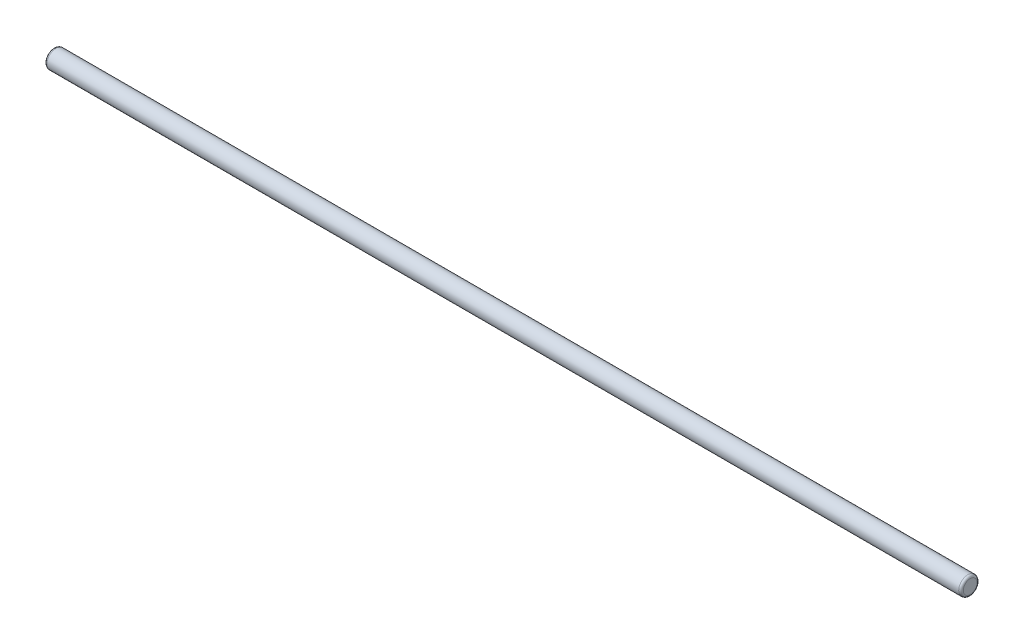
SolidWorks part; units mm, degrees
ref_plane "Front Plane" through (0, 0, 0) normal (0, 0, 1) x (1, 0, 0)
ref_plane "Top Plane" through (0, 0, 0) normal (0, 1, 0) x (1, 0, 0)
ref_plane "Right Plane" through (0, 0, 0) normal (1, 0, 0) x (0, 0, -1)
sketch "ProfileSketch1" plane through (0, 0, 0) normal (1, 0, 0) x (0, 0, -1)
  circle A0 centre (0, 0) radius 4
  dimension "D1" = 8
extrude "ProfileBoss-Extrude1" add sketch "ProfileSketch1" along normal blind 400
fillet "Fillet1" radius 1 2 edges at (0, 0, -4) (400, 0, -4)
equation "\"RodShaft8mmDiameter\"= 8mm"
equation "\"RodShaft400mmLength\"= 400mm"
equation "\"D1@ProfileBoss-Extrude1\" = \"RodShaft400mmLength\""
equation "\"D1@ProfileSketch1\"=\"RodShaft8mmDiameter\""
